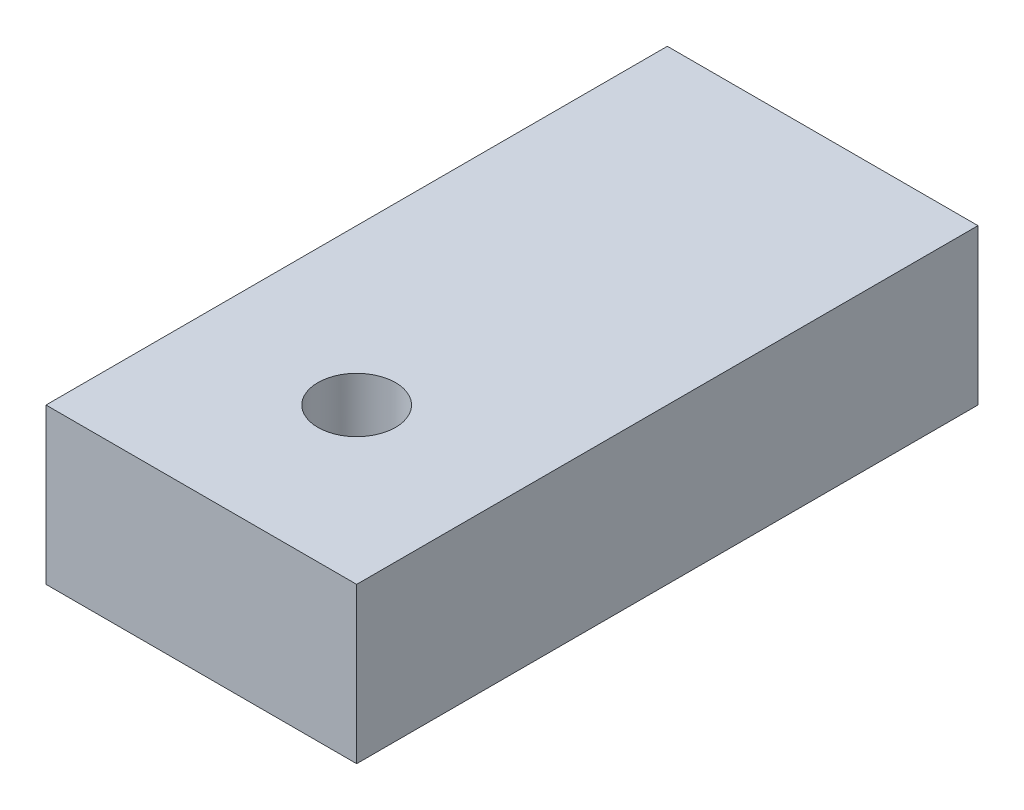
SolidWorks part; units mm, degrees
ref_plane "Front Plane" through (0, 0, 0) normal (0, 0, 1) x (1, 0, 0)
ref_plane "Top Plane" through (0, 0, 0) normal (0, 1, 0) x (1, 0, 0)
ref_plane "Right Plane" through (0, 0, 0) normal (1, 0, 0) x (0, 0, -1)
sketch "Sketch1" plane through (0, 0, 0) normal (0, 0, 1) x (1, 0, 0)
  line L1 (0, 0) -> (50.8, 0)
  line L2 (0, 0) -> (0, 25.4)
  line L3 (0, 25.4) -> (50.8, 25.4)
  line L4 (50.8, 0) -> (50.8, 25.4)
  dimension "D1" = 50.8
  dimension "D2" = 25.4
extrude "Boss-Extrude1" add sketch "Sketch1" along normal blind 101.6
sketch "Sketch2" plane through (0, 25.4, 0) normal (0, 1, 0) x (1, 0, 0)
  line L0 (50.8, -101.6) -> (0, -101.6) construction
  circle A0 centre (25.4, -76.2) radius 6.35
  point P2 (0, 0)
  point P5 (0, 0)
  point P6 (25.4, -101.6)
  point P7 (0, 0)
  point P8 (0, 0)
  point P9 (0, 0)
  dimension "D1" = 12.7
  dimension "D2" = 25.4
extrude "Cut-Extrude1" cut sketch "Sketch2" against normal through all both and the other way through all contours A0
